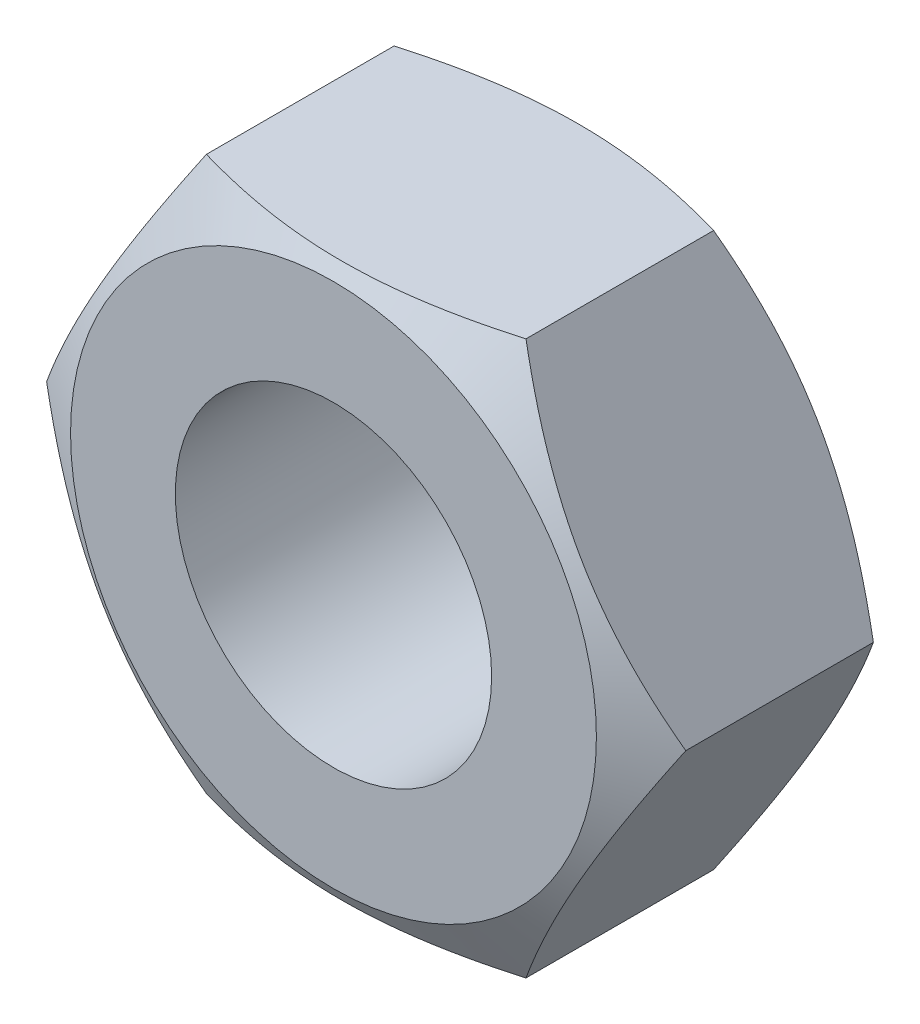
SolidWorks part; units mm, degrees
ref_plane "Plane1" through (0, 0, 0) normal (0, 0, 1) x (1, 0, 0)
ref_plane "Plane2" through (0, 0, 0) normal (0, 1, 0) x (1, 0, 0)
ref_plane "Plane3" through (0, 0, 0) normal (1, 0, 0) x (0, 0, -1)
sketch "BaseNutSke" plane through (0, 0, 0) normal (0, 0, 1) x (1, 0, 0)
  line L6 (2.0207, -3.5) -> (-2.0207, -3.5)
  line L7 (2.0207, 3.5) -> (-2.0207, 3.5)
  line L8 (2.0207, -3.5) -> (4.0415, 0)
  line L9 (4.0415, 0) -> (2.0207, 3.5)
  line L10 (-2.0207, 3.5) -> (-4.0415, 0)
  line L11 (-4.0415, 0) -> (-2.0207, -3.5)
  circle A0 centre (0, 0) radius 1.65 construction
  circle A1 centre (0, 0) radius 4.0415 construction
  circle A2 centre (0, 0) radius 2
  dimension "Tap_drill" = 3.3
  dimension "Diameter" = 4
  dimension "Width_flats" = 7
extrude "BaseNut" add sketch "BaseNutSke" against normal blind 3.2
cosmetic thread "ThreadCosmetic" [suppressed] parameters "Thread_major"=4
ref_plane "Plane4" through (0, 0, -1.6) normal (0, 0, -1) x (-1, 0, 0)
sketch "Sketch6" plane through (0, 0, -3.2) normal (0, 0, -1) x (-1, 0, 0)
  circle A0 centre (0, 0) radius 3.325
  dimension "D1" = 6.65
extrude "Cut-Extrude2" cut sketch "Sketch6" against normal through all draft 60 flip side to cut
mirror "Mirror1" about plane through (0, 0, -1.6) normal (0, 0, -1) of "Cut-Extrude2"
sketch "Sketch7" plane through (0, 0, 0) normal (1, 0, 0) x (0, 0, -1)
  line L0 (0.4, 13.5) -> (0.4, 3.15)
  line L1 (0.4, 3.15) -> (0, 3.15)
  line L2 (0, 0) -> (0, 3.5) construction
  line L3 (0, 3.15) -> (0, 13.5)
  line L5 (2.7864, 3.5) -> (0.4136, 3.5) construction
  line L6 (0, 13.5) -> (0.4, 13.5)
  line L7 (0, 0) -> (8.1777, 0) construction
  line L8 (2.7864, 0) -> (0.4136, 0) construction
  dimension "D1" = 10
  dimension "Dw" = 6.3
  dimension "hw" = 0.4
revolve "Bearing-Face" [suppressed] cut sketch "Sketch7" angle 360 about L7
equation "\"D1@Sketch3\" = \"Width_flats@BaseNutSke\" /2"
equation "' \"Num_threads@ThdSchPat\" = \"Num_threads@ThdSchPat\" - sgn( \"Num_threads@ThdSchPat\" - 1) '---chamfered tips only---"
equation "\"D1@Sketch6\" = 0.95 * \"Width_flats@BaseNutSke\""
